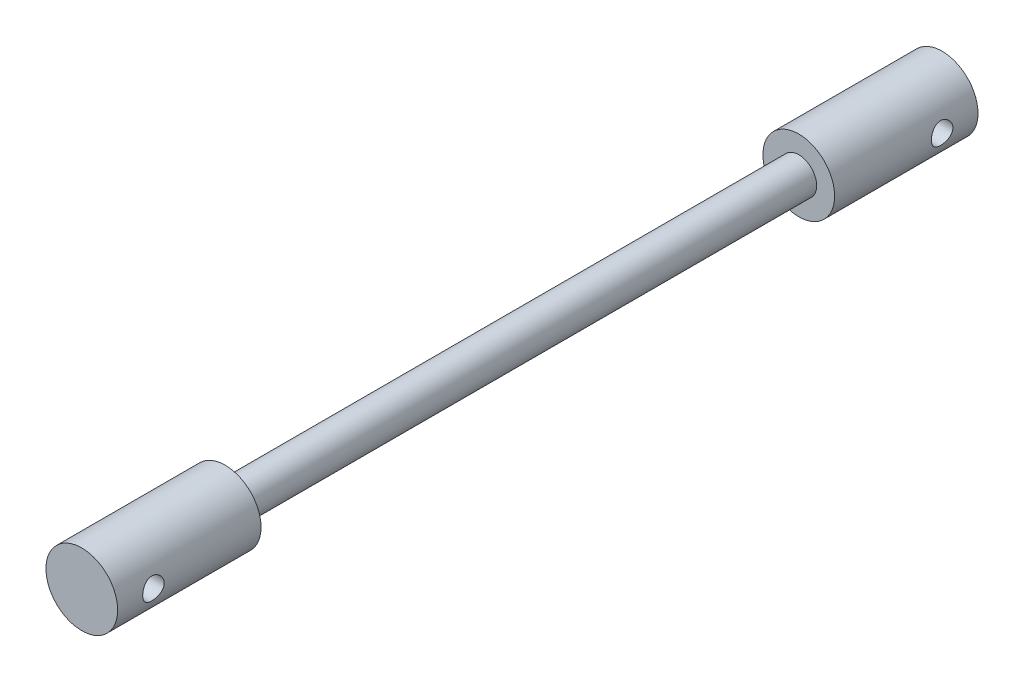
SolidWorks part; units mm, degrees
ref_plane "Front Plane" through (0, 0, 0) normal (0, 0, 1) x (1, 0, 0)
ref_plane "Top Plane" through (0, 0, 0) normal (0, 1, 0) x (1, 0, 0)
ref_plane "Right Plane" through (0, 0, 0) normal (1, 0, 0) x (0, 0, -1)
sketch "Sketch1" plane through (0, 0, 0) normal (0, 0, 1) x (1, 0, 0)
  circle A0 centre (0, 0) radius 5
  dimension "D1" = 10
extrude "Boss-Extrude1" add sketch "Sketch1" along normal blind 20
sketch "Sketch3" plane through (0, 0, 20) normal (0, 0, 1) x (1, 0, 0)
  circle A0 centre (0, 0) radius 2.5
  dimension "D1" = 5
extrude "Boss-Extrude2" add sketch "Sketch3" along normal blind 40
ref_plane "Plane1" through (5, 0, 0) normal (1, 0, 0) x (0, 0, -1)
sketch "Sketch7" plane through (5, 0, 0) normal (1, 0, 0) x (0, 0, -1)
  line L0 (0, 0) -> (-20, 0) construction
  line L1 (-20, 5) -> (-20, -5) construction
  circle A0 centre (-5, 0) radius 1.5
  dimension "D1" = 3
  dimension "D2" = 5
extrude "Cut-Extrude1" cut sketch "Sketch7" against normal through all
ref_plane "Plane2" through (0, 0, 60) normal (0, 0, 1) x (1, 0, 0)
mirror "Mirror4" about plane through (0, 0, 60) normal (0, 0, 1) of "Boss-Extrude2"
mirror "Mirror5" about plane through (0, 0, 60) normal (0, 0, 1) of "Boss-Extrude1"
sketch "Sketch9" plane through (5, 0, 0) normal (1, 0, 0) x (0, 0, -1)
  line L0 (0, 0) -> (-120, 0) construction
  line L1 (-120, 5) -> (-120, -5) construction
  circle A0 centre (-115, 0) radius 1.5
  dimension "D1" = 3
  dimension "D2" = 5
extrude "Cut-Extrude2" cut sketch "Sketch9" against normal through all
